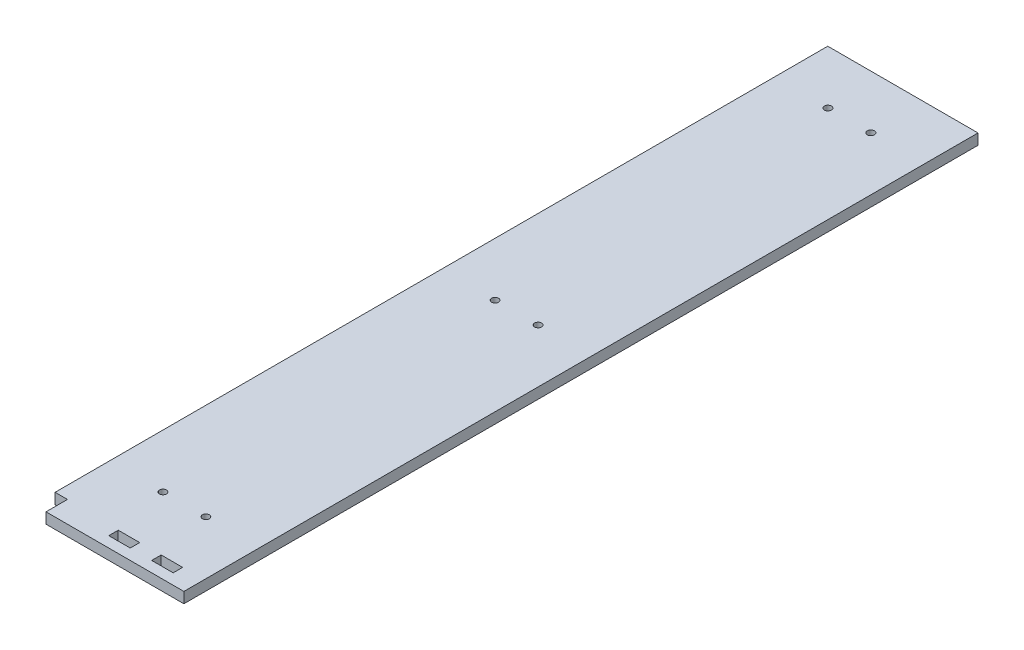
SolidWorks part; units mm, degrees
material "Pine"
ref_plane "Front Plane" through (0, 0, 0) normal (0, 0, 1) x (1, 0, 0)
ref_plane "Top Plane" through (0, 0, 0) normal (0, 1, 0) x (1, 0, 0)
ref_plane "Right Plane" through (0, 0, 0) normal (1, 0, 0) x (0, 0, -1)
sketch "Sketch1" plane through (0, 0, 0) normal (0, 0, 1) x (1, 0, 0)
  line L0 (-44.45, 38.1) -> (-44.45, 24.5485) construction
  line L1 (44.45, -38.1) -> (-44.45, -38.1)
  line L2 (44.45, -38.1) -> (44.45, -44.45)
  line L3 (44.45, -44.45) -> (-44.45, -44.45)
  line L4 (-44.45, -38.1) -> (-44.45, -44.45)
  dimension "D1" = 6.35
extrude "Boss-Extrude1" add sketch "Sketch1" against normal up to surface (457.2 mm away)
sketch "Sketch2" plane through (0, -44.45, 0) normal (0, -1, 0) x (1, 0, 0)
  circle A0 centre (-12.7, -228.6) radius 2.0638
  circle A1 centre (-12.7, -228.6) radius 2.0638 construction
  circle A2 centre (12.7, -228.6) radius 2.0638
  circle A3 centre (12.7, -228.6) radius 2.0638 construction
  circle A4 centre (-12.7, -32.0675) radius 2.0638
  circle A5 centre (-12.7, -32.0675) radius 2.0638 construction
  circle A6 centre (12.7, -32.0675) radius 2.0638
  circle A7 centre (12.7, -32.0675) radius 2.0638 construction
extrude "Cut-Extrude1" cut sketch "Sketch2" against normal through all
sketch "Sketch3" plane through (0, -44.45, 0) normal (0, -1, 0) x (-1, 0, 0)
  circle A0 centre (12.7, 425.5516) radius 2.0955
  circle A1 centre (-12.7, 425.5516) radius 2.0955
  circle A2 centre (-12.7, 425.5516) radius 2.0955 construction
  circle A3 centre (12.7, 425.5516) radius 2.0955 construction
extrude "Cut-Extrude2" cut sketch "Sketch3" against normal through all
sketch "Sketch4" plane through (0, 0, 0) normal (0, 0, 1) x (1, 0, 0)
  line L0 (44.45, -38.1) -> (-44.45, -38.1) construction
  line L1 (44.45, -44.45) -> (-37.1407, -44.45)
  line L2 (44.45, -44.45) -> (44.45, -38.1)
  line L3 (44.45, -38.1) -> (-37.1407, -38.1)
  line L4 (-37.1407, -44.45) -> (-37.1407, -38.1)
extrude "Boss-Extrude2" add sketch "Sketch4" along normal blind 12.7
sketch "Sketch5" plane through (0, -44.45, 0) normal (0, -1, 0) x (1, 0, 0)
  line L0 (44.45, -457.2) -> (44.45, 12.7) construction
  line L1 (31.75, 0.7434) -> (19.05, 0.7434)
  line L2 (31.75, 0.7434) -> (31.75, 6.35)
  line L3 (31.75, 6.35) -> (19.05, 6.35)
  line L4 (19.05, 0.7434) -> (19.05, 6.35)
  line L5 (6.35, 0.7434) -> (-6.35, 0.7434)
  line L6 (6.35, 0.7434) -> (6.35, 6.35)
  line L7 (6.35, 6.35) -> (-6.35, 6.35)
  line L8 (-6.35, 0.7434) -> (-6.35, 6.35)
  line L9 (-37.1407, 12.7) -> (44.45, 12.7) construction
  dimension "D1" = 12.7
  dimension "D2" = 12.7
  dimension "D3" = 12.7
  dimension "D4" = 12.7
  dimension "D5" = 6.35
extrude "Cut-Extrude3" cut sketch "Sketch5" against normal blind 12.7
